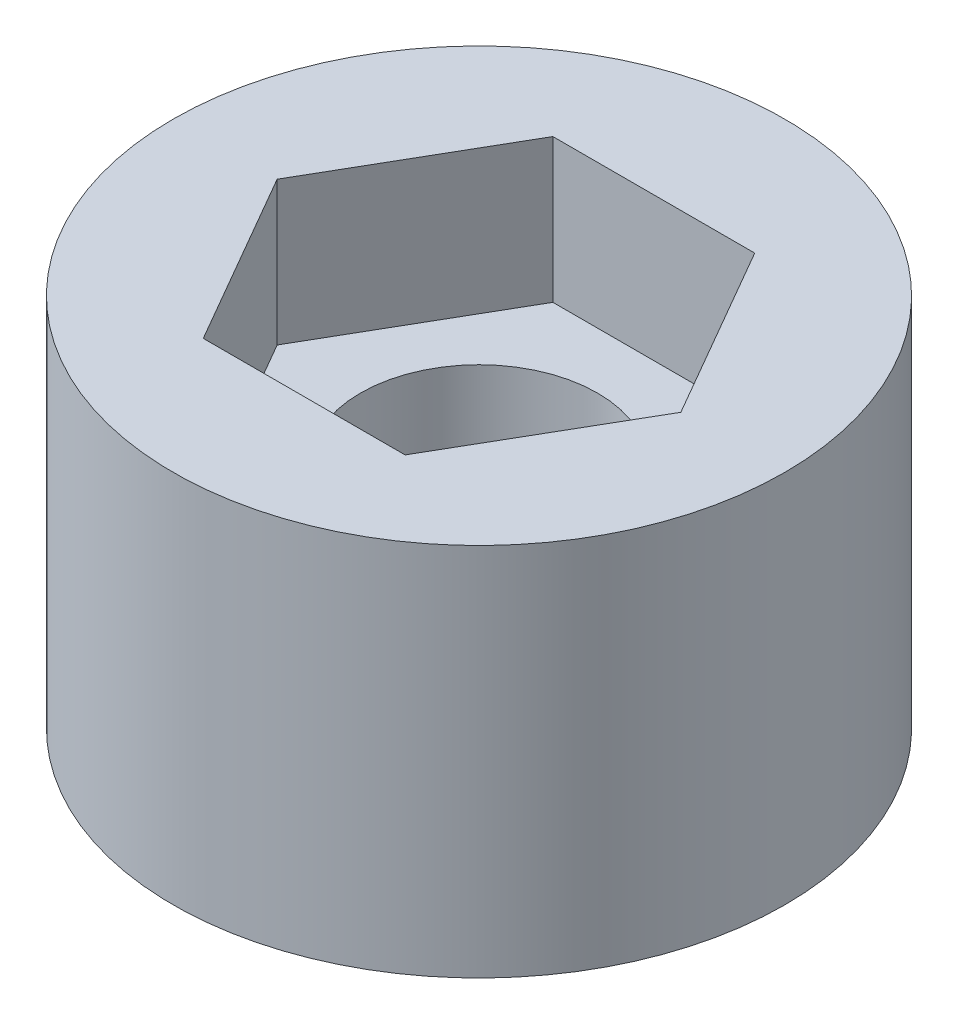
SolidWorks part; units mm, degrees
ref_plane "Front Plane" through (0, 0, 0) normal (0, 0, 1) x (1, 0, 0)
ref_plane "Top Plane" through (0, 0, 0) normal (0, 1, 0) x (1, 0, 0)
ref_plane "Right Plane" through (0, 0, 0) normal (1, 0, 0) x (0, 0, -1)
sketch "Sketch1" plane through (0, 0, 0) normal (0, 1, 0) x (1, 0, 0)
  circle A0 centre (0, 0) radius 1.9
  dimension "D1" = 3.8
extrude "Extrude-Thin1" add sketch "Sketch1" along normal blind 6 thin
sketch "Sketch2" plane through (0, 6, 0) normal (0, 1, 0) x (1, 0, 0)
  line L1 (3.2332, 0) -> (1.6166, 2.8)
  line L2 (1.6166, 2.8) -> (-1.6166, 2.8)
  line L3 (-1.6166, 2.8) -> (-3.2332, 0)
  line L4 (-3.2332, 0) -> (-1.6166, -2.8)
  line L5 (-1.6166, -2.8) -> (1.6166, -2.8)
  line L6 (1.6166, -2.8) -> (3.2332, 0)
  circle A0 centre (0, 0) radius 2.8 construction
  dimension "D1" = 5.6
extrude "Cut-Extrude1" cut sketch "Sketch2" against normal blind 2.3
